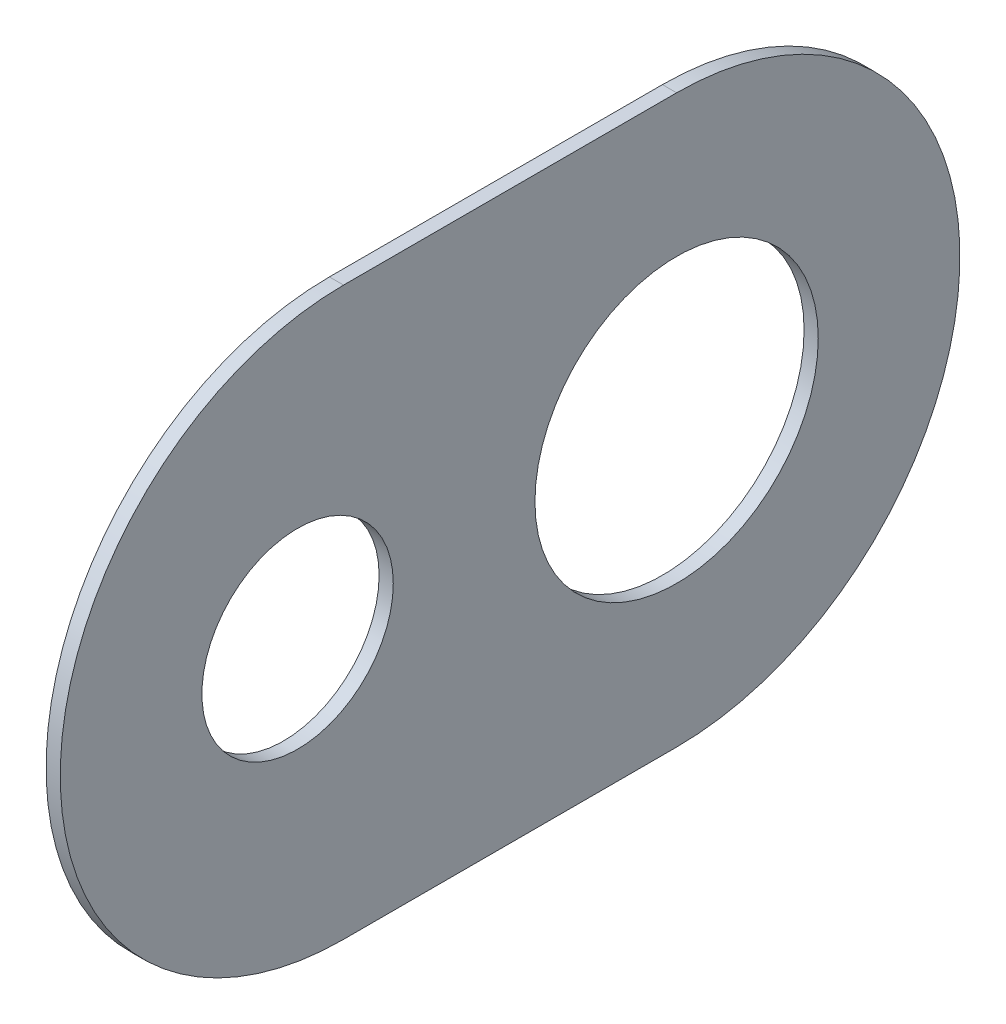
SolidWorks part; units mm, degrees
material "Ti-6Al-4VSolution treated and aged (SS)"
ref_plane "Front Plane" through (0, 0, 0) normal (1, 0, 0) x (0, 1, 0)
ref_plane "Top Plane" through (0, 0, 0) normal (0, 0, 1) x (0, 1, 0)
ref_plane "Right Plane" through (0, 0, 0) normal (0, 1, 0) x (-1, 0, 0)
sketch "Sketch1" plane through (0, 0, 0) normal (1, 0, 0) x (0, 1, 0)
  line L0 (0, -14.9288) -> (0, 14.9288) construction
  line L1 (-25.4, -14.9288) -> (-25.4, 14.9288)
  line L2 (25.4, -14.9288) -> (25.4, 14.9288)
  line L3 (0, 27.6288) -> (0, 40.3288) construction
  line L4 (0, 40.3288) -> (0, -27.6288) construction
  line L5 (0, -27.6288) -> (0, -40.3288) construction
  line L6 (12.7, -14.9288) -> (25.4, -14.9288) construction
  arc A0 (-25.4, -14.9288) -> (25.4, -14.9288) centre (0, -14.9288) ccw
  arc A1 (25.4, 14.9288) -> (-25.4, 14.9288) centre (0, 14.9288) ccw
  circle A2 centre (0, 19.05) radius 8.5789
  circle A3 centre (0, -14.9288) radius 12.7
  point P2 (0, 0)
  point P18 (0, 10.4711)
  point P19 (0, -2.2288)
  dimension "D1" = 25.4
  dimension "D2" = 17.1577
  dimension "D3" = 12.7
  dimension "D4" = 12.7
  dimension "D5" = 12.7
  dimension "D6" = 12.7
extrude "Boss-Extrude1" add sketch "Sketch1" along normal blind 1.27
equation "\"E\"= 15199999.87'Titainium Grade 5 Modulus of Elasticity"
equation "\"s\"= 120000.0006'Titanium Grade 5 Yield strength"
equation "\"dmax\"= 0.005'maximum allowable deflection"
equation "\"F\"= 750'Load"
equation "\"Sf\"= 4'Safety Factor"
equation "\"cxs\"= ( \"F\" * \"Sf\" ) / ( \"s\" * 0.05 ) 'Minimum material edge to edge length"
equation "\"Lmin\"= ( \"cxs\" * 3 ) + 1.0005 + 0.6643 'Maximum Length"
equation "\"Lmax\"= ( \"cxs\" * 3 ) + 1.000 + 0.6633'Minimum Length"
equation "\"Lavg\"= 0.5 * ( \"Lmin\" + \"Lmax\" )'Average Length"
equation "\"D3@Sketch1\"=\"cxs\""
equation "\"D4@Sketch1\"=\"cxs\""
equation "\"D5@Sketch1\"=\"cxs\""
equation "\"D6@Sketch1\"=\"cxs\""
